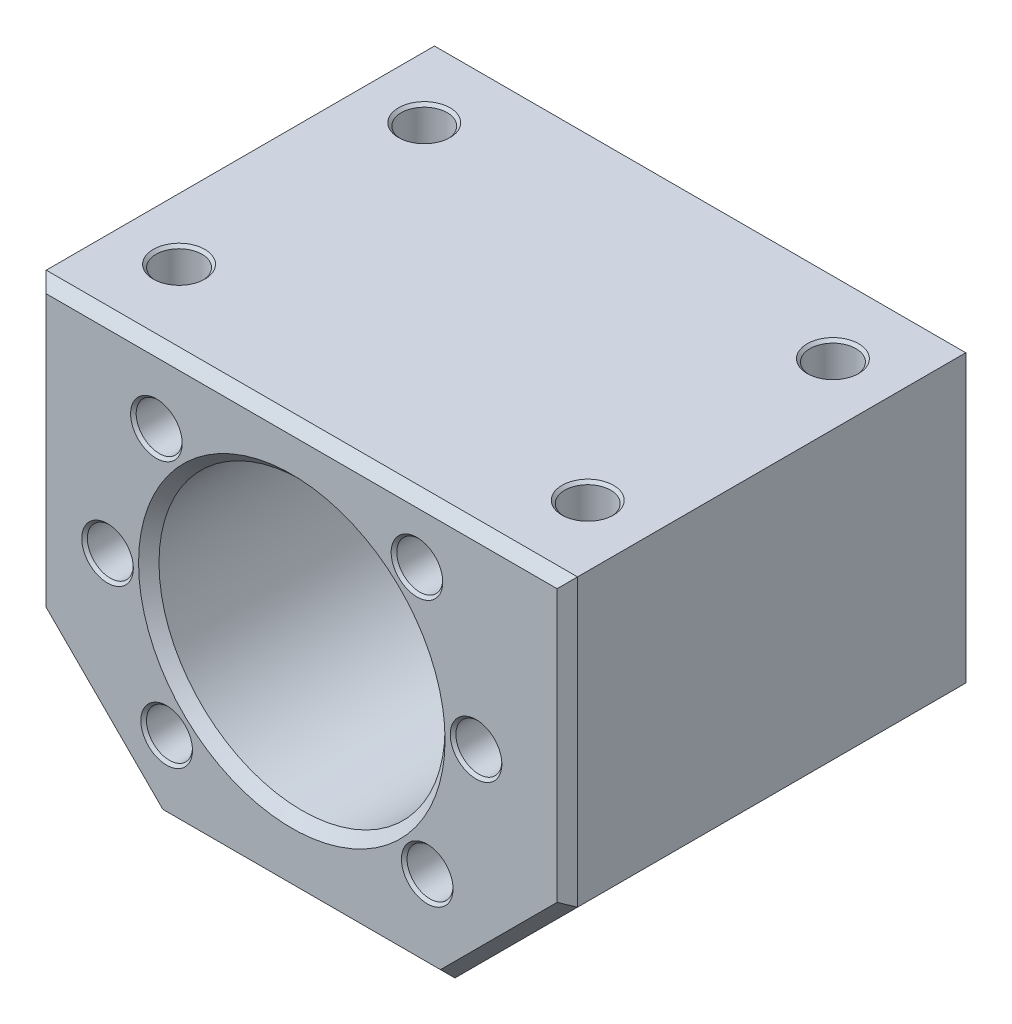
SolidWorks part; units mm, degrees
ref_plane "Front Plane" through (0, 0, 0) normal (0, 0, 1) x (1, 0, 0)
ref_plane "Top Plane" through (0, 0, 0) normal (0, 1, 0) x (1, 0, 0)
ref_plane "Right Plane" through (0, 0, 0) normal (1, 0, 0) x (0, 0, -1)
sketch "Sketch1" plane through (0, 0, 0) normal (0, 0, 1) x (1, 0, 0)
  line L0 (-49.5944, 39.1269) -> (2.4056, 39.1269)
  line L1 (2.4056, 39.1269) -> (2.4056, 11.1269)
  line L2 (2.4056, 11.1269) -> (-9.5944, -0.8731)
  line L3 (-9.5944, -0.8731) -> (-37.5944, -0.8731)
  line L4 (-37.5944, -0.8731) -> (-49.5944, 11.1269)
  line L5 (-49.5944, 11.1269) -> (-49.5944, 39.1269)
  dimension "D1" = 40
  dimension "D2" = 12
  dimension "D3" = 52
  dimension "D4" = 12
  dimension "D5" = 28
  dimension "D6" = 135
extrude "Boss-Extrude1" add sketch "Sketch1" along normal blind 40
sketch "Sketch2" plane through (0, 0, 40) normal (0, 0, 1) x (1, 0, 0)
  circle A0 centre (-24.559, 19.8376) radius 14
  circle A1 centre (-24.559, 19.8376) radius 19
  dimension "D1" = 28
  dimension "D2" = 38
extrude "Cut-Extrude1" cut sketch "Sketch2" against normal blind 40 contours A0
hole_wizard "M5x0.5 Tapped Hole4" positions "Sketch12" profile "Sketch11" tap size "M5x0.5" standard "DIN"
sketch "Sketch12" plane through (0, 39.1269, 0) normal (0, 1, 0) x (1, 0, 0)
  line L0 (-49.5944, -40) -> (-49.5944, 0) construction
  line L1 (2.4056, -40) -> (-49.5944, -40) construction
  line L2 (2.4056, -40) -> (2.4056, 0) construction
  point P0 (-43.5944, -32)
  point P2 (-3.5944, -32)
  point P4 (-3.5944, -8)
  point P6 (-43.5944, -8)
  dimension "D1" = 6
  dimension "D2" = 40
  dimension "D3" = 8
  dimension "D4" = 24
  dimension "D5" = 8
  dimension "D6" = 6
  dimension "D7" = 24
  dimension "D8" = 40
sketch "Sketch11" plane through (-43.5944, 39.1269, 32) normal (1, 0, 0) x (0, 0, 1)
  line L0 (0, 0) -> (0, 12.8519)
  line L1 (0, 12.8519) -> (2.25, 11.5)
  line L2 (2.25, 11.5) -> (2.25, 0.275)
  line L3 (2.25, 0.275) -> (2.525, 0)
  line L5 (2.525, 0) -> (0, 0)
  line L6 (-2.25, 0.275) -> (-2.525, 0) construction
  line L10 (0, 12.8519) -> (-2.25, 11.5) construction
  line L11 (0, -6.35) -> (0, 107.95) construction
  dimension "Tap Drill Dia." = 4.5
  dimension "Tap Drill Depth" = 11.5
  dimension "Near C'Sink Dia." = 5.05
  dimension "Near C'Sink Angle" = 90
  dimension "Drill Angle" = 118
hole_wizard "M5x0.5 Tapped Hole5" positions "Sketch14" profile "Sketch15" tap size "M5x0.5" standard "DIN"
sketch "Sketch14" plane through (0, 0, 40) normal (0, 0, 1) x (1, 0, 0)
  line L0 (2.4056, 39.1269) -> (-49.5944, 39.1269) construction
  line L1 (-49.5944, 39.1269) -> (-49.5944, 11.1269) construction
  circle A0 centre (-23.5266, 19.1269) radius 19
  point P0 (-42.5944, 19.1269)
  dimension "D3" = 38
  dimension "D1" = 20
  dimension "D2" = 7
sketch "Sketch15" plane through (-42.5944, 19.1269, 40) normal (1, 0, 0) x (0, -1, 0)
  line L0 (0, 0) -> (0, 7.3519)
  line L1 (0, 7.3519) -> (2.25, 6)
  line L2 (2.25, 6) -> (2.25, 0.275)
  line L3 (2.25, 0.275) -> (2.525, 0)
  line L5 (2.525, 0) -> (0, 0)
  line L6 (-2.25, 0.275) -> (-2.525, 0) construction
  line L10 (0, 7.3519) -> (-2.25, 6) construction
  line L11 (0, -6.35) -> (0, 107.95) construction
  dimension "Tap Drill Dia." = 4.5
  dimension "Tap Drill Depth" = 6
  dimension "Near C'Sink Dia." = 5.05
  dimension "Near C'Sink Angle" = 90
  dimension "Drill Angle" = 118
cosmetic thread "Hole Thread8" parameters "D1"=10, "D2"=5
pattern_circular "CirPattern1" count 8 over 360 about axis through (-24.559, 19.8376, 0) along (0, 0, 1) skipping 2, 6 of "M5x0.5 Tapped Hole5"
fillet "Chamfer1" radius 1 12 edges at (-3.5944, 5.1269, 0) (2.4056, 25.1269, 0) (-23.5944, 39.1269, 0) (-49.5944, 25.1269, 0) (-43.5944, 5.1269, 0) (-23.5944, -0.8731, 0) (-3.5944, 5.1269, 40) (2.4056, 25.1269, 40) (-23.5944, -0.8731, 40) (-43.5944, 5.1269, 40) (-23.5944, 39.1269, 40) (-49.5944, 25.1269, 40) profile chamfer
chamfer "Chamfer2" distance 1 angle 45 2 edges at (-10.559, 19.8376, 0) (-10.559, 19.8376, 40)
